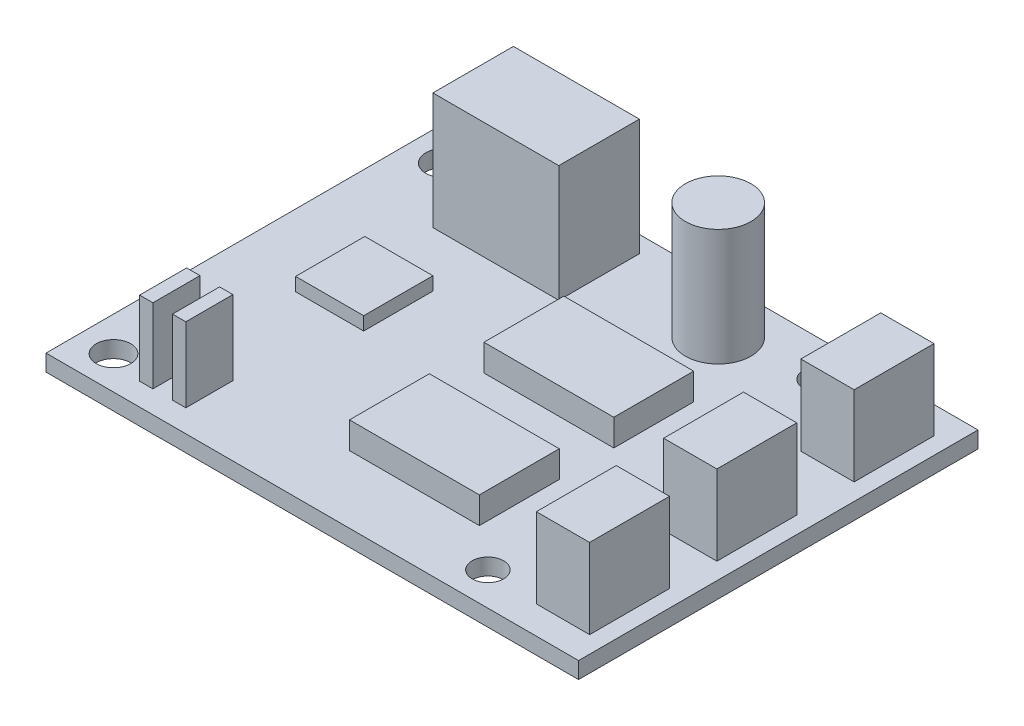
SolidWorks part; units mm, degrees
ref_plane "Front Plane" through (0, 0, 0) normal (0, 0, 1) x (1, 0, 0)
ref_plane "Top Plane" through (0, 0, 0) normal (0, 1, 0) x (1, 0, 0)
ref_plane "Right Plane" through (0, 0, 0) normal (1, 0, 0) x (0, 0, -1)
sketch "Sketch1" plane through (0, 0, 0) normal (0, 1, 0) x (1, 0, 0)
  line L1 (0, 0) -> (50.8, 0)
  line L2 (0, 0) -> (0, 38.1)
  line L3 (0, 38.1) -> (50.8, 38.1)
  line L4 (50.8, 0) -> (50.8, 38.1)
extrude "Boss-Extrude1" add sketch "Sketch1" along normal blind 1.5748
sketch "Sketch2" plane through (0, 1.5748, 0) normal (0, 1, 0) x (1, 0, 0)
  line L1 (44.1099, 2.6644) -> (49.1899, 2.6644)
  line L2 (44.1099, 2.6644) -> (44.1099, 10.2844)
  line L3 (44.1099, 10.2844) -> (49.1899, 10.2844)
  line L4 (49.1899, 2.6644) -> (49.1899, 10.2844)
  line L5 (49.1899, 14.8036) -> (44.1099, 14.8036)
  line L6 (49.1899, 14.8036) -> (49.1899, 22.4236)
  line L7 (49.1899, 22.4236) -> (44.1099, 22.4236)
  line L8 (44.1099, 14.8036) -> (44.1099, 22.4236)
  line L9 (44.1099, 27.8935) -> (49.1899, 27.8935)
  line L10 (44.1099, 27.8935) -> (44.1099, 35.5135)
  line L11 (44.1099, 35.5135) -> (49.1899, 35.5135)
  line L12 (49.1899, 27.8935) -> (49.1899, 35.5135)
  dimension "D1" = 5.08
  dimension "D2" = 7.62
  dimension "D3" = 7.62
  dimension "D4" = 7.62
extrude "Boss-Extrude2" add sketch "Sketch2" along normal blind 7.62
sketch "Sketch3" plane through (0, 1.5748, 0) normal (0, 1, 0) x (1, 0, 0)
  line L1 (8.0853, 36.5) -> (20.0974, 36.5)
  line L2 (8.0853, 36.5) -> (8.0853, 28.8166)
  line L3 (8.0853, 28.8166) -> (20.0974, 28.8166)
  line L4 (20.0974, 36.5) -> (20.0974, 28.8166)
  circle A0 centre (30.7567, 33.3617) radius 3.1275
extrude "Boss-Extrude3" add sketch "Sketch3" along normal blind 11.1252
sketch "Sketch4" plane through (0, 1.5748, 0) normal (0, 1, 0) x (1, 0, 0)
  line L1 (22.5323, 26.8594) -> (34.9231, 26.8594)
  line L2 (22.5323, 26.8594) -> (22.5323, 19.2394)
  line L3 (22.5323, 19.2394) -> (34.9231, 19.2394)
  line L4 (34.9231, 26.8594) -> (34.9231, 19.2394)
  line L5 (22.5323, 14.0357) -> (34.9231, 14.0357)
  line L6 (22.5323, 14.0357) -> (22.5323, 6.4157)
  line L7 (22.5323, 6.4157) -> (34.9231, 6.4157)
  line L8 (34.9231, 14.0357) -> (34.9231, 6.4157)
  dimension "D1" = 7.62
  dimension "D2" = 7.62
extrude "Boss-Extrude4" add sketch "Sketch4" along normal blind 2.54
sketch "Sketch5" plane through (0, 1.5748, 0) normal (0, 1, 0) x (1, 0, 0)
  line L1 (6.8408, 23.5681) -> (13.3338, 23.5681)
  line L2 (6.8408, 23.5681) -> (6.8408, 16.9668)
  line L3 (6.8408, 16.9668) -> (13.3338, 16.9668)
  line L4 (13.3338, 23.5681) -> (13.3338, 16.9668)
extrude "Boss-Extrude5" add sketch "Sketch5" along normal blind 1.27
sketch "Sketch6" plane through (0, 1.5748, 0) normal (0, 1, 0) x (1, 0, 0)
  line L1 (6.7867, 6.6321) -> (8.0567, 6.6321)
  line L2 (6.7867, 6.6321) -> (6.7867, 2.1411)
  line L3 (6.7867, 2.1411) -> (8.0567, 2.1411)
  line L4 (8.0567, 6.6321) -> (8.0567, 2.1411)
  line L5 (9.925, 6.6321) -> (11.195, 6.6321)
  line L6 (9.925, 6.6321) -> (9.925, 2.1411)
  line L7 (9.925, 2.1411) -> (11.195, 2.1411)
  line L8 (11.195, 6.6321) -> (11.195, 2.1411)
  dimension "D1" = 1.27
  dimension "D2" = 1.27
extrude "Boss-Extrude6" add sketch "Sketch6" along normal blind 7.112
sketch "Sketch7" plane through (0, 1.5748, 0) normal (0, 1, 0) x (1, 0, 0)
  circle A0 centre (3.2696, 3.1692) radius 1.6456
  circle A1 centre (38.9812, 3.1692) radius 1.5005
  circle A2 centre (38.9812, 34.6603) radius 1.4295
  circle A3 centre (3.2696, 34.6603) radius 1.704
  point P8 (2.5121, 34.6603)
  point P9 (3.2696, 2.4658)
  point P10 (38.9812, 2.4658)
  point P11 (3.2696, 34.6603)
  point P12 (3.2696, 3.1692)
  point P13 (38.9812, 3.1692)
extrude "Cut-Extrude1" cut sketch "Sketch7" against normal blind 7.112
